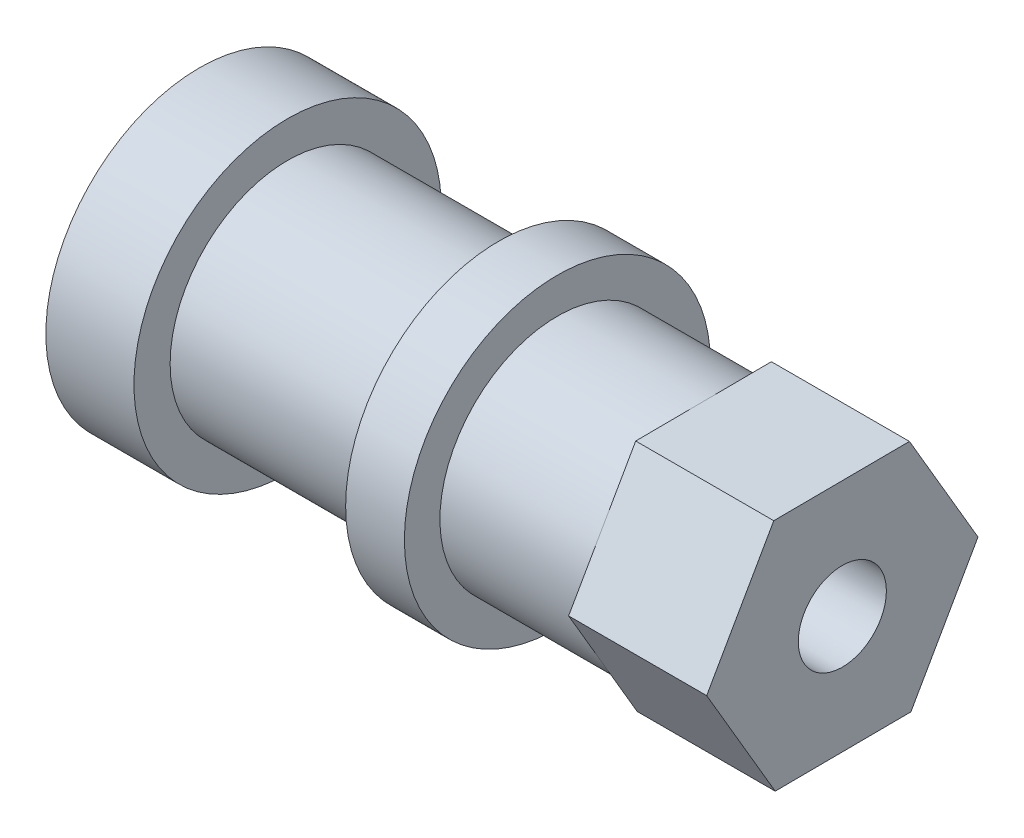
SolidWorks part; units mm, degrees
ref_plane "Front Plane" through (0, 0, 0) normal (0, 0, 1) x (1, 0, 0)
ref_plane "Top Plane" through (0, 0, 0) normal (0, 1, 0) x (1, 0, 0)
ref_plane "Right Plane" through (0, 0, 0) normal (1, 0, 0) x (0, 0, -1)
sketch "Sketch1" plane through (0, 0, 0) normal (1, 0, 0) x (0, 0, -1)
  line L1 (2.3344, -3.9855) -> (4.6187, 0.0289)
  line L2 (4.6187, 0.0289) -> (2.2844, 4.0144)
  line L3 (2.2844, 4.0144) -> (-2.3344, 3.9855)
  line L4 (-2.3344, 3.9855) -> (-4.6187, -0.0289)
  line L5 (-4.6187, -0.0289) -> (-2.2844, -4.0144)
  line L6 (-2.2844, -4.0144) -> (2.3344, -3.9855)
  circle A0 centre (0, 0) radius 4 construction
  dimension "D1" = 8
  dimension "D2" = 9.2374
extrude "Boss-Extrude1" add sketch "Sketch1" along normal blind 4.7 contours L5 L6 L1 L2 L3 L4
sketch "Sketch3" plane through (0, 0, 0) normal (-1, 0, 0) x (0, 0, 1)
  circle A0 centre (0, 0) radius 4
  circle A1 centre (0, 0) radius 1.5
  dimension "D1" = 8
  dimension "D2" = 3
extrude "Boss-Extrude2" add sketch "Sketch3" along normal up to surface (17.185 mm away)
sketch "Sketch4" plane through (-17.185, 0, 0) normal (-1, 0, 0) x (0, 0, 1)
  circle A0 centre (0, 0) radius 5.231
extrude "Boss-Extrude3" add sketch "Sketch4" against normal blind 3
sketch "Sketch2" plane through (4.7, 0, 0) normal (1, 0, 0) x (0, 0, -1)
  circle A0 centre (0, 0) radius 1.5
  dimension "D1" = 3
extrude "Cut-Extrude1" cut sketch "Sketch2" against normal through all both and the other way through all
sketch "Sketch6" plane through (-17.185, 0, 0) normal (-1, 0, 0) x (0, 0, 1)
  line L1 (0, -2.8868) -> (2.5, -1.4434)
  line L2 (2.5, -1.4434) -> (2.5, 1.4434)
  line L3 (2.5, 1.4434) -> (0, 2.8868)
  line L4 (0, 2.8868) -> (-2.5, 1.4434)
  line L5 (-2.5, 1.4434) -> (-2.5, -1.4434)
  line L6 (-2.5, -1.4434) -> (0, -2.8868)
  circle A0 centre (0, 0) radius 2.5 construction
  dimension "D1" = 5
sketch "Sketch7" plane through (0, 0, 0) normal (1, 0, 0) x (0, 0, -1)
  circle A0 centre (0, 0) radius 5.2095
  circle A1 centre (0, 0) radius 1.5
  dimension "D1" = 3
extrude "Cut-Extrude4" cut sketch "Sketch6" against normal blind 2
extrude "Boss-Extrude5" add sketch "Sketch7" along normal blind 2 from surface
